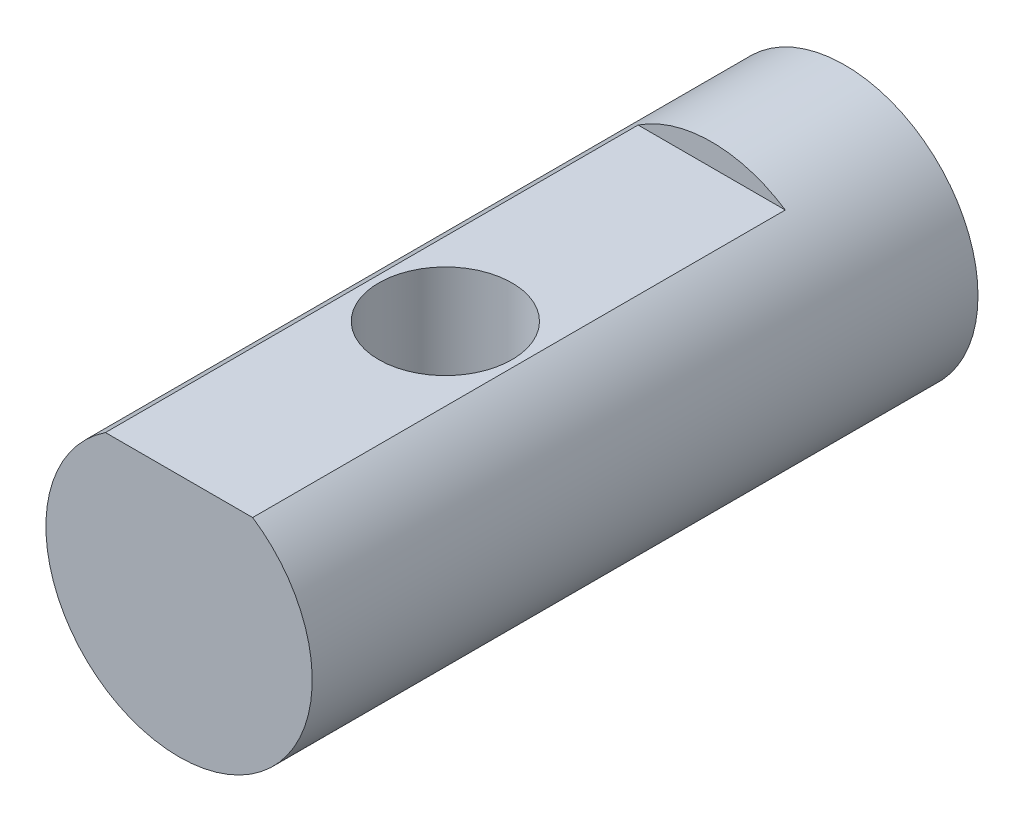
SolidWorks part; units mm, degrees
ref_plane "Front Plane" through (0, 0, 0) normal (0, 0, 1) x (1, 0, 0)
ref_plane "Top Plane" through (0, 0, 0) normal (0, 1, 0) x (1, 0, 0)
ref_plane "Right Plane" through (0, 0, 0) normal (1, 0, 0) x (0, 0, -1)
sketch "Sketch1" plane through (0, 0, 0) normal (0, 0, 1) x (1, 0, 0)
  circle A0 centre (0, 0) radius 3
  dimension "D1" = 6
extrude "Boss-Extrude1" add sketch "Sketch1" along normal blind 15
sketch "Sketch2" plane through (0, 0, 15) normal (0, 0, 1) x (1, 0, 0)
  line L0 (-1.6583, 2.5) -> (1.6583, 2.5)
  arc A0 (1.6583, 2.5) -> (-1.6583, 2.5) centre (0, 0) ccw
  dimension "D1" = 2.5
extrude "Cut-Extrude1" cut sketch "Sketch2" against normal blind 12
sketch "Sketch3" plane through (0, 2.5, 0) normal (0, 1, 0) x (1, 0, 0)
  line L0 (-1.6583, -3) -> (1.6583, -3) construction
  circle A0 centre (0, -9) radius 1.5
  dimension "D1" = 3
  dimension "D2" = 6
extrude "Cut-Extrude2" cut sketch "Sketch3" against normal blind 6
